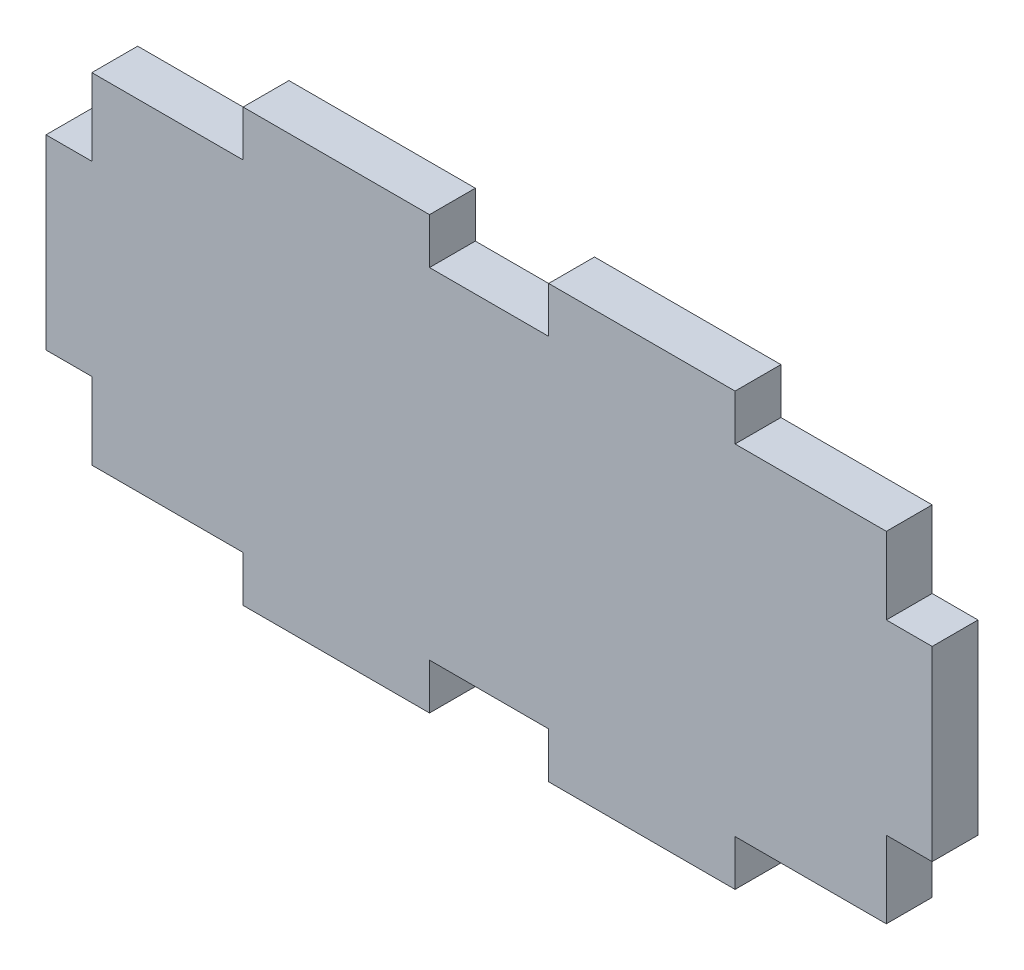
SolidWorks part; units mm, degrees
material "Acrylic (Medium-high impact)"
ref_plane "Front Plane" through (0, 0, 0) normal (0, 0, 1) x (1, 0, 0)
ref_plane "Top Plane" through (0, 0, 0) normal (0, 1, 0) x (1, 0, 0)
ref_plane "Right Plane" through (0, 0, 0) normal (1, 0, 0) x (0, 0, -1)
sketch "Sketch2" plane through (0, 0, 0) normal (0, 0, 1) x (1, 0, 0)
  line L0 (32.9, 0) -> (45.1, 0)
  line L1 (12.9, 0) -> (25.1, 0)
  line L2 (0, 8.025) -> (0, 20.225)
  line L3 (12.9, 28.25) -> (25.1, 28.25)
  line L4 (58, 8.025) -> (58, 20.225)
  line L5 (3, 3) -> (12.9, 3)
  line L8 (45.1, 3) -> (55, 3)
  line L10 (32.9, 28.25) -> (45.1, 28.25)
  line L11 (3, 25.25) -> (12.9, 25.25)
  line L12 (3, 20.225) -> (3, 25.25)
  line L14 (12.9, 0) -> (12.9, 3)
  line L16 (25.1, 0) -> (25.1, 3)
  line L17 (25.1, 3) -> (32.9, 3)
  line L18 (45.1, 3) -> (45.1, 0)
  line L20 (32.9, 3) -> (32.9, 0)
  line L21 (45.1, 25.25) -> (55, 25.25)
  line L22 (12.9, 25.25) -> (12.9, 28.25)
  line L24 (25.1, 25.25) -> (25.1, 28.25)
  line L26 (32.9, 28.25) -> (32.9, 25.25)
  line L27 (0, 20.225) -> (3, 20.225)
  line L28 (45.1, 28.25) -> (45.1, 25.25)
  line L29 (25.1, 25.25) -> (32.9, 25.25)
  line L31 (0, 8.025) -> (3, 8.025)
  line L32 (55, 20.225) -> (55, 25.25)
  line L33 (3, 8.025) -> (3, 3)
  line L34 (58, 20.225) -> (55, 20.225)
  line L36 (58, 8.025) -> (55, 8.025)
  line L38 (55, 8.025) -> (55, 3)
  dimension "D1" = 12.2
  dimension "D2" = 12.2
  dimension "D3" = 3
  dimension "D4" = 3
  dimension "D5" = 12.2
  dimension "D6" = 12.9
  dimension "D7" = 12.9
  dimension "D8" = 28.25
  dimension "D9" = 5.025
  dimension "D10" = 3
  dimension "D11" = 3
  dimension "D12" = 12.2
  dimension "D13" = 7.8
  dimension "D14" = 7.8
  dimension "D15" = 12.2
  dimension "D16" = 12.2
  dimension "D17" = 9.9
  dimension "D18" = 5.025
extrude "Boss-Extrude1" add sketch "Sketch2" along normal blind 3
